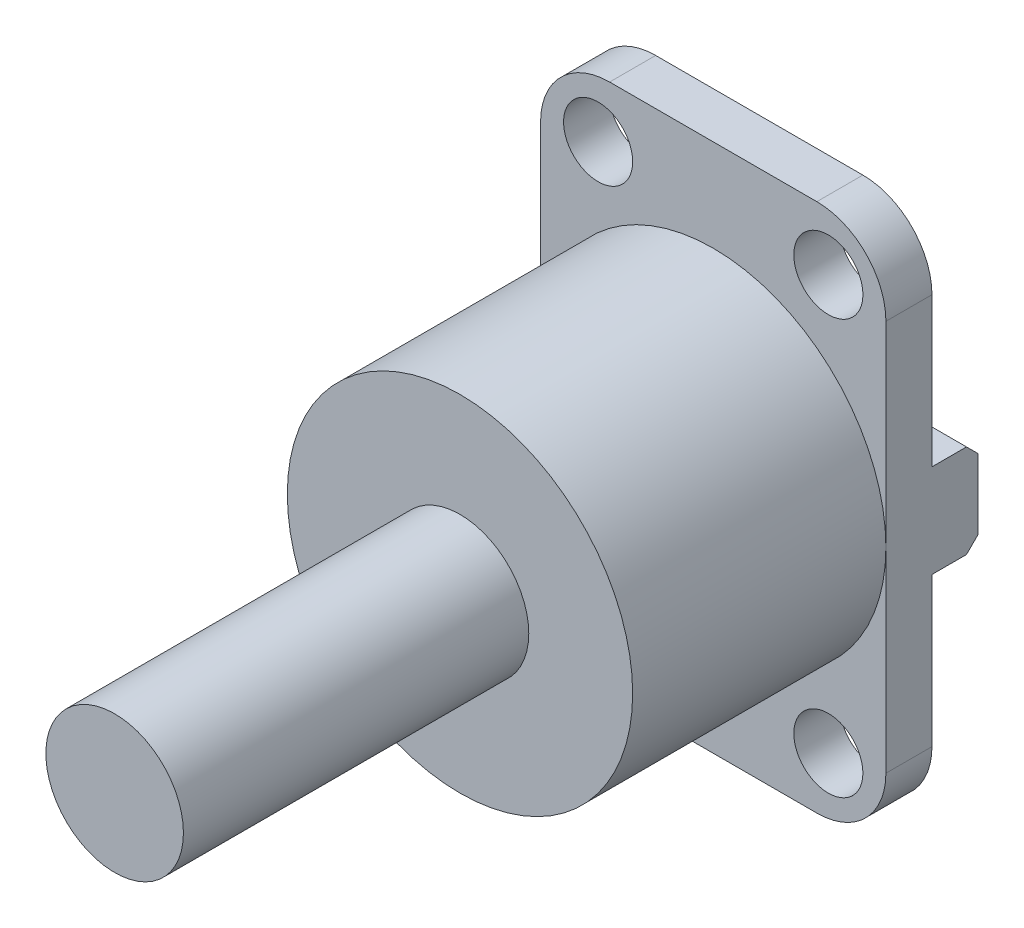
SolidWorks part; units mm, degrees
ref_plane "Front Plane" through (0, 0, 0) normal (0, 0, 1) x (1, 0, 0)
ref_plane "Top Plane" through (0, 0, 0) normal (0, 1, 0) x (1, 0, 0)
ref_plane "Right Plane" through (0, 0, 0) normal (1, 0, 0) x (0, 0, -1)
sketch "Sketch1" plane through (0, 0, 0) normal (0, 0, 1) x (1, 0, 0)
  line L0 (0, 15.3056) -> (0, -14.8354) construction
  line L1 (-23.1818, 0) -> (19.6552, 0) construction
  line L3 (-7.5, 11.5) -> (7.5, 11.5)
  line L4 (-7.5, 11.5) -> (-7.5, -11.5)
  line L5 (-7.5, -11.5) -> (7.5, -11.5)
  line L6 (7.5, 11.5) -> (7.5, -11.5)
  circle A0 centre (-5, 9) radius 1.5
  circle A1 centre (5, 9) radius 1.5
  circle A2 centre (5, -9) radius 1.5
  circle A3 centre (-5, -9) radius 1.5
  dimension "D5" = 3
  dimension "D6" = 5
  dimension "D7" = 9
  dimension "D1" = 15
  dimension "D2" = 7.5
  dimension "D3" = 11.5
  dimension "D4" = 11.5
extrude "Boss-Extrude1" add sketch "Sketch1" along normal blind 2
sketch "Sketch2" plane through (0, 0, 2) normal (0, 0, 1) x (1, 0, 0)
  circle A0 centre (0, 0) radius 7.5
  dimension "D1" = 15
extrude "Boss-Extrude2" add sketch "Sketch2" along normal blind 11
sketch "Sketch3" plane through (0, 0, 13) normal (0, 0, 1) x (1, 0, 0)
  circle A0 centre (0, 0) radius 2.9875
  dimension "D1" = 5.975
extrude "Boss-Extrude3" add sketch "Sketch3" along normal blind 15
sketch "Sketch4" plane through (0, 0, 0) normal (0, 0, -1) x (-1, 0, 0)
  line L0 (-11.1733, 0) -> (11.1121, 0) construction
  line L1 (0, 14.2161) -> (0, -13.8635) construction
  line L2 (-7.5, -11.5) -> (-7.5, 11.5) construction
  line L3 (-7.5, 2.025) -> (7.5, 2.025)
  line L4 (-7.5, 2.025) -> (-7.5, -2.025)
  line L5 (-7.5, -2.025) -> (7.5, -2.025)
  line L6 (7.5, 2.025) -> (7.5, -2.025)
  line L7 (7.5, 11.5) -> (7.5, -11.5) construction
  dimension "D1" = 4.05
  dimension "D2" = 2.025
extrude "Boss-Extrude4" add sketch "Sketch4" along normal blind 2
chamfer "Chamfer1" distance 0.5 2 edges at (0, -2.025, -2) (0, 2.025, -2)
fillet "Fillet1" radius 3 4 edges at (-7.5, -11.5, 1) (7.5, -11.5, 1) (-7.5, 11.5, 1) (7.5, 11.5, 1)
